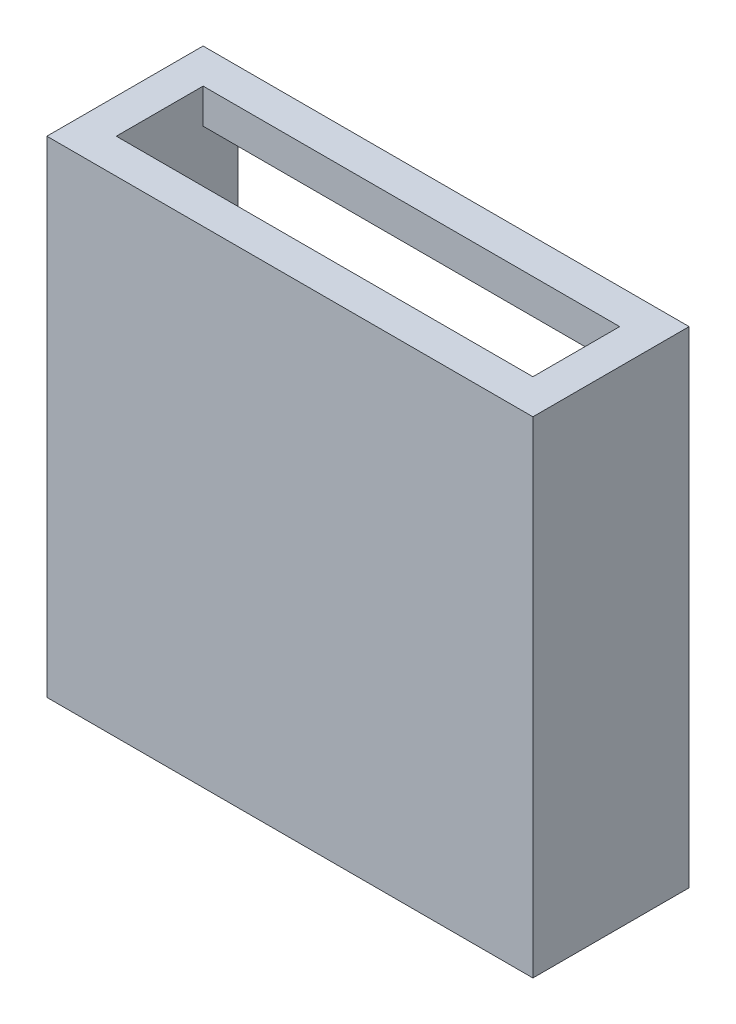
SolidWorks part; units mm, degrees
material "ABS"
ref_plane "Спереди" through (0, 0, 0) normal (0, 0, 1) x (1, 0, 0)
ref_plane "Сверху" through (0, 0, 0) normal (0, 1, 0) x (1, 0, 0)
ref_plane "Справа" through (0, 0, 0) normal (1, 0, 0) x (0, 0, -1)
sketch "Эскиз1" plane through (0, 0, 0) normal (0, 0, 1) x (1, 0, 0)
  line L1 (-14, 14) -> (14, 14)
  line L2 (-14, 14) -> (-14, -14)
  line L3 (-14, -14) -> (14, -14)
  line L4 (14, 14) -> (14, -14)
  line L5 (-14, 14) -> (14, -14) construction
  line L6 (-14, -14) -> (14, 14) construction
  point P0 (0, 0)
  dimension "D1" = 28
  dimension "D2" = 28
extrude "Бобышка-Вытянуть1" add sketch "Эскиз1" along normal blind 2
sketch "Эскиз2" plane through (0, 0, 0) normal (0, 0, -1) x (-1, 0, 0)
  line L0 (12, 12) -> (-12, 12)
  line L1 (14, -14) -> (-14, -14)
  line L2 (14, -14) -> (14, 14)
  line L3 (14, 14) -> (-14, 14)
  line L4 (-14, -14) -> (-14, 14)
  line L5 (14, -14) -> (-14, 14) construction
  line L6 (14, 14) -> (-14, -14) construction
  line L7 (-12, -12) -> (-12, 12)
  line L8 (12, -12) -> (-12, -12)
  line L9 (12, -12) -> (12, 12)
  point P0 (0, 0)
  dimension "D1" = 2
extrude "Бобышка-Вытянуть2" add sketch "Эскиз2" along normal blind 7
sketch "Эскиз3" plane through (0, 14, 0) normal (0, 1, 0) x (1, 0, 0)
  line L0 (0, -2) -> (0, 7) construction
  line L1 (14, -2) -> (-14, -2) construction
  line L2 (-14, 7) -> (14, 7) construction
  line L3 (-14, -2) -> (-14, 7) construction
  line L4 (12, 0) -> (-12, 0)
  line L5 (12, 0) -> (12, 5)
  line L6 (12, 5) -> (-12, 5)
  line L7 (-12, 0) -> (-12, 5)
  line L8 (12, 0) -> (-12, 5) construction
  line L9 (12, 5) -> (-12, 0) construction
  point P6 (0, 2.5)
  dimension "D1" = 2
  dimension "D2" = 2
extrude "Вырез-Вытянуть1" cut sketch "Эскиз3" against normal through all
sketch "Эскиз4" plane through (0, 0, 0) normal (0, 0, -1) x (-1, 0, 0)
  line L0 (0, 0) -> (0, 1.25) construction
  line L1 (1.9651, -1.5964) -> (-0.2, -0.3464)
  line L2 (-0.4, 2.5) -> (0.4, 2.5)
  line L3 (-0.4, 2.5) -> (-0.4, 0)
  line L4 (-0.4, 0) -> (0.4, 0)
  line L5 (0.4, 2.5) -> (0.4, 0)
  line L6 (-0.4, 2.5) -> (0.4, 0) construction
  line L7 (-0.4, 0) -> (0.4, 2.5) construction
  line L8 (2.3651, -0.9036) -> (1.9651, -1.5964)
  line L9 (2.3651, -0.9036) -> (0.2, 0.3464)
  line L10 (0.2, 0.3464) -> (-0.2, -0.3464)
  line L11 (-2.3651, -0.9036) -> (-0.2, 0.3464)
  line L12 (-1.9651, -1.5964) -> (-2.3651, -0.9036)
  line L13 (-1.9651, -1.5964) -> (0.2, -0.3464)
  line L14 (0.2, -0.3464) -> (-0.2, 0.3464)
  circle A0 centre (0, 0) radius 0.4
  point P19 (0, 0)
  dimension "D1" = 0.8
  dimension "D2" = 2.5
  dimension "D3" = 0.8
extrude "Бобышка-Вытянуть3" add sketch "Эскиз4" along normal blind 3.5 contours A0 L3 L11 L12 L13 L1 | A0 L13 L1 L8 L9 L5 | A0 L9 L5 L2 L3 L11 | L10 A0 L14 | L14 A0 L4 | L4 A0 L10 | L14 A0 L4 | L10 A0 L14 | L4 A0 L10 | A0 L1 L13 | A0 L5 L9 | A0 L11 L3
sketch "Эскиз6" plane through (0, 0, 0) normal (0, 1, 0) x (1, 0, 0)
  line L0 (-12, 2.5) -> (-12, 6) construction
  line L1 (-12, 5) -> (-12, 0) construction
  line L2 (-12, 6) -> (-10.5, 4)
  line L3 (-10.5, 4) -> (-12, 4)
  line L4 (-12, 4) -> (-12, 6)
  line L5 (14, 7) -> (-14, 7) construction
  dimension "D1" = 1.5
  dimension "D2" = 2
  dimension "D3" = 1
extrude "Бобышка-Вытянуть4" add sketch "Эскиз6" along normal blind 4 and the other way blind 4
mirror "Зеркальное отражение1" about plane through (0, 0, 0) normal (1, 0, 0) of "Бобышка-Вытянуть4"
sketch "Эскиз7" plane through (0, 0, -3.5) normal (0, 0, -1) x (-1, 0, 0)
  circle A0 centre (0, 0) radius 1.7893 construction
